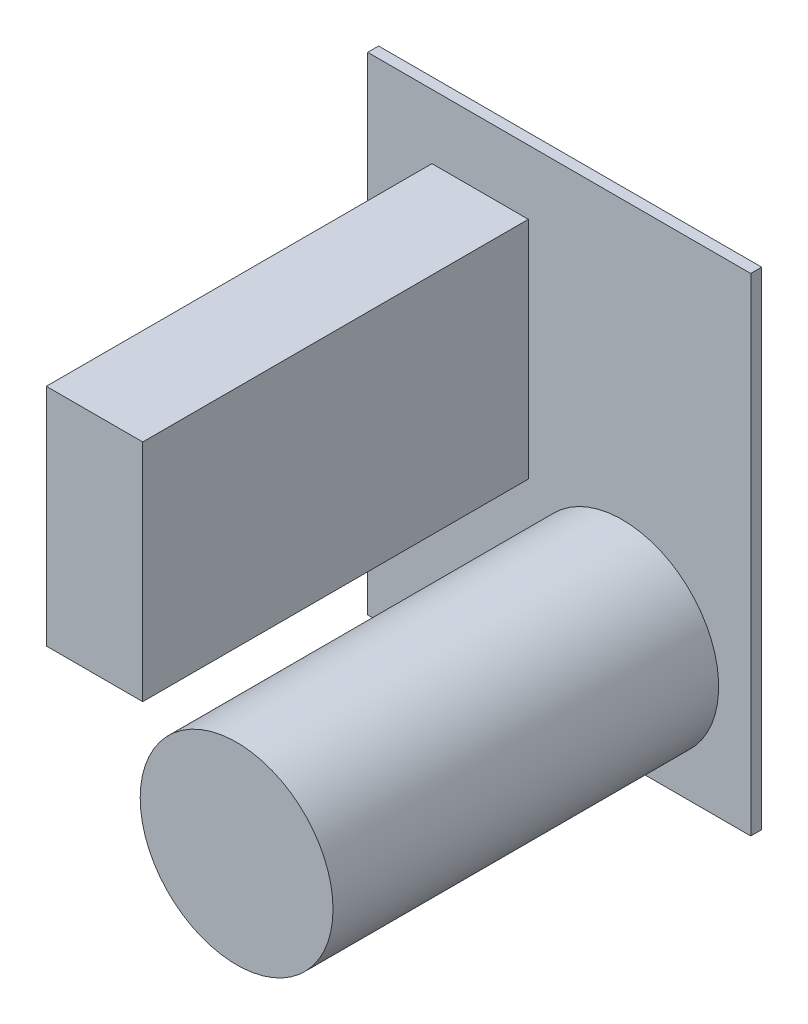
SolidWorks part; units mm, degrees
ref_plane "Plano frontal" through (0, 0, 0) normal (0, 0, 1) x (1, 0, 0)
ref_plane "Plano superior" through (0, 0, 0) normal (0, 1, 0) x (1, 0, 0)
ref_plane "Plano direito" through (0, 0, 0) normal (1, 0, 0) x (0, 0, -1)
sketch "Esboço1" plane through (0, 0, 0) normal (0, 0, 1) x (1, 0, 0)
  line L1 (0, 0) -> (59.6, 0)
  line L2 (0, 0) -> (0, 75.8)
  line L3 (0, 75.8) -> (59.6, 75.8)
  line L4 (59.6, 0) -> (59.6, 75.8)
  dimension "D1" = 59.6
  dimension "D2" = 75.8
extrude "Ressalto-extrusão1" add sketch "Esboço1" along normal blind 1.7
sketch3d "3DSketch1"
  point P0 (24.9122, 64.5781, 1.7)
ref_plane "Plano1" through (0, 0, 1.7) normal (0, 0, 1) x (1, 0, 0)
sketch "Esboço2" plane through (0, 0, 1.7) normal (0, 0, 1) x (1, 0, 0)
  line L0 (59.6, 75.8) -> (0, 75.8) construction
  line L1 (10, 65.8) -> (25, 65.8)
  line L2 (10, 65.8) -> (10, 30.8)
  line L3 (10, 30.8) -> (25, 30.8)
  line L4 (25, 65.8) -> (25, 30.8)
  line L5 (0, 75.8) -> (0, 0) construction
  dimension "D1" = 10
  dimension "D2" = 10
  dimension "D3" = 35
  dimension "D4" = 15
extrude "Ressalto-extrusão2" add sketch "Esboço2" along normal blind 60
sketch3d "3DSketch2" [suppressed]
  point P0 (10, 56.1961, 10.2519)
ref_plane "Plano2" [suppressed] through (10, 0, 0) normal (-1, 0, 0) x (0, 0, 1)
sketch "Esboço4" [suppressed] plane through (10, 0, 0) normal (-1, 0, 0) x (0, 0, 1)
  line L0 (1.7, -29.1844) -> (1.7, 29.1844) construction
  line L1 (16.7, 65.8) -> (1.7, 65.8)
  line L2 (16.7, 65.8) -> (16.7, 30.8)
  line L3 (16.7, 30.8) -> (1.7, 30.8)
  line L4 (1.7, 65.8) -> (1.7, 30.8)
  line L5 (16.7, 30.8) -> (1.7, 30.8) construction
extrude "Ressalto-extrusão3" [suppressed] add sketch "Esboço4" along normal blind 45
sketch "Esboço5" plane through (0, 0, 1.7) normal (0, 0, 1) x (1, 0, 0)
  circle A0 centre (39.6053, 17.6395) radius 15
extrude "Ressalto-extrusão4" add sketch "Esboço5" along normal blind 60
